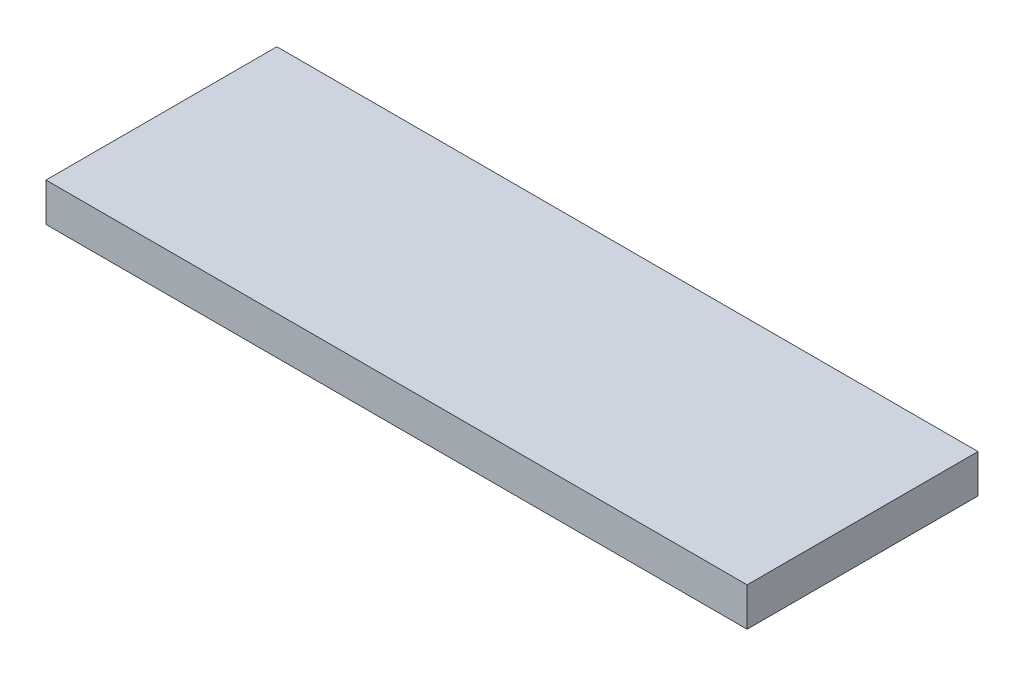
SolidWorks part; units mm, degrees
ref_plane "Přední rovina" through (0, 0, 0) normal (0, 0, 1) x (1, 0, 0)
ref_plane "Horní rovina" through (0, 0, 0) normal (0, 1, 0) x (1, 0, 0)
ref_plane "Pravá rovina" through (0, 0, 0) normal (1, 0, 0) x (0, 0, -1)
sketch "Skica1" plane through (0, 0, 0) normal (0, 1, 0) x (1, 0, 0)
  line L1 (-82, -27) -> (82, -27)
  line L2 (-82, -27) -> (-82, 27)
  line L3 (-82, 27) -> (82, 27)
  line L4 (82, -27) -> (82, 27)
  line L5 (-82, -27) -> (82, 27) construction
  line L6 (-82, 27) -> (82, -27) construction
  point P0 (0, 0)
  dimension "D1" = 54
  dimension "D2" = 164
extrude "Přidat vysunutím1" add sketch "Skica1" along normal blind 9
